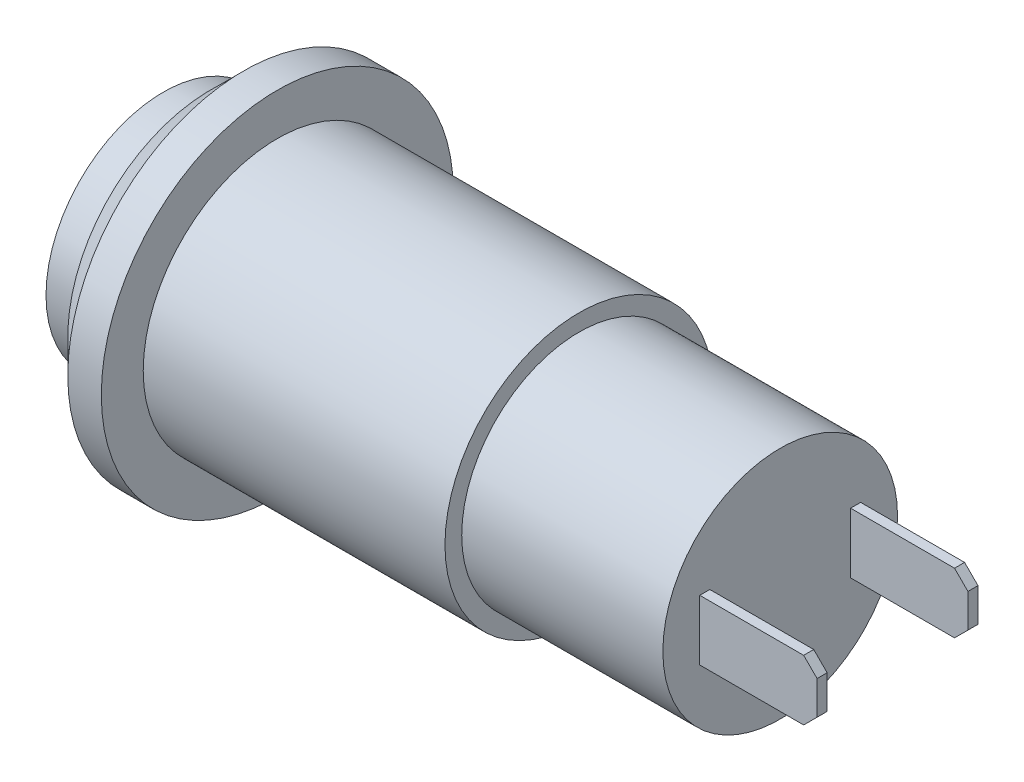
SolidWorks part; units mm, degrees
ref_plane "前视基准面" through (0, 0, 0) normal (0, 0, 1) x (1, 0, 0)
ref_plane "上视基准面" through (0, 0, 0) normal (0, 1, 0) x (1, 0, 0)
ref_plane "右视基准面" through (0, 0, 0) normal (1, 0, 0) x (0, 0, -1)
sketch "草图1" plane through (0, 0, 0) normal (0, 0, 1) x (1, 0, 0)
  line L0 (-10.9846, 0) -> (11.3077, 0) construction
  line L1 (0, 0) -> (0, 3.5)
  line L2 (0, 3.5) -> (1.4, 3.5)
  line L3 (1.4, 3.5) -> (1.4, 5.25)
  line L4 (1.4, 5.25) -> (3.4, 5.25)
  line L5 (3.4, 5.25) -> (3.4, 4)
  line L6 (3.4, 4) -> (12.4, 4)
  line L7 (12.4, 4) -> (12.4, 3.5)
  line L8 (12.4, 3.5) -> (18.4, 3.5)
  line L9 (18.4, 3.5) -> (18.4, 0)
  line L10 (0, 0) -> (18.4, 0)
  point P10 (0.7, 3.5)
  point P14 (0, 0)
  dimension "D1" = 2
  dimension "D2" = 1.4
  dimension "D3" = 9
  dimension "D4" = 7
  dimension "D5" = 7
  dimension "D6" = 8
  dimension "D7" = 10.5
  dimension "D8" = 18.4
revolve "旋转1" add sketch "草图1" angle 360 about L0
cosmetic thread "装饰螺纹线1" parameters "D2"=6.647
chamfer "倒角1" distance 1 angle 45 1 edges at (1.4, 0, 5.25)
sketch "草图2" plane through (18.4, 0, 0) normal (1, 0, 0) x (0, 0, -1)
  line L0 (-2.25, 0) -> (2.25, 0) construction
  line L2 (-2.1, -0.9) -> (-2.4, -0.9)
  line L3 (-2.1, -0.9) -> (-2.1, 0.9)
  line L4 (-2.1, 0.9) -> (-2.4, 0.9)
  line L5 (-2.4, -0.9) -> (-2.4, 0.9)
  line L6 (-2.1, -0.9) -> (-2.4, 0.9) construction
  line L7 (-2.1, 0.9) -> (-2.4, -0.9) construction
  line L8 (2.4, -0.9) -> (2.1, -0.9)
  line L9 (2.4, -0.9) -> (2.4, 0.9)
  line L10 (2.4, 0.9) -> (2.1, 0.9)
  line L11 (2.1, -0.9) -> (2.1, 0.9)
  line L12 (2.4, -0.9) -> (2.1, 0.9) construction
  line L13 (2.4, 0.9) -> (2.1, -0.9) construction
  point P4 (0, 0)
  dimension "D1" = 1.8
  dimension "D2" = 0.3
  dimension "D3" = 4.8
extrude "凸台-拉伸1" add sketch "草图2" along normal blind 3.5
chamfer "倒角2" distance 0.4 angle 45 4 edges at (21.9, -0.9, -2.25) (21.9, 0.9, -2.25) (21.9, -0.9, 2.25) (21.9, 0.9, 2.25)
